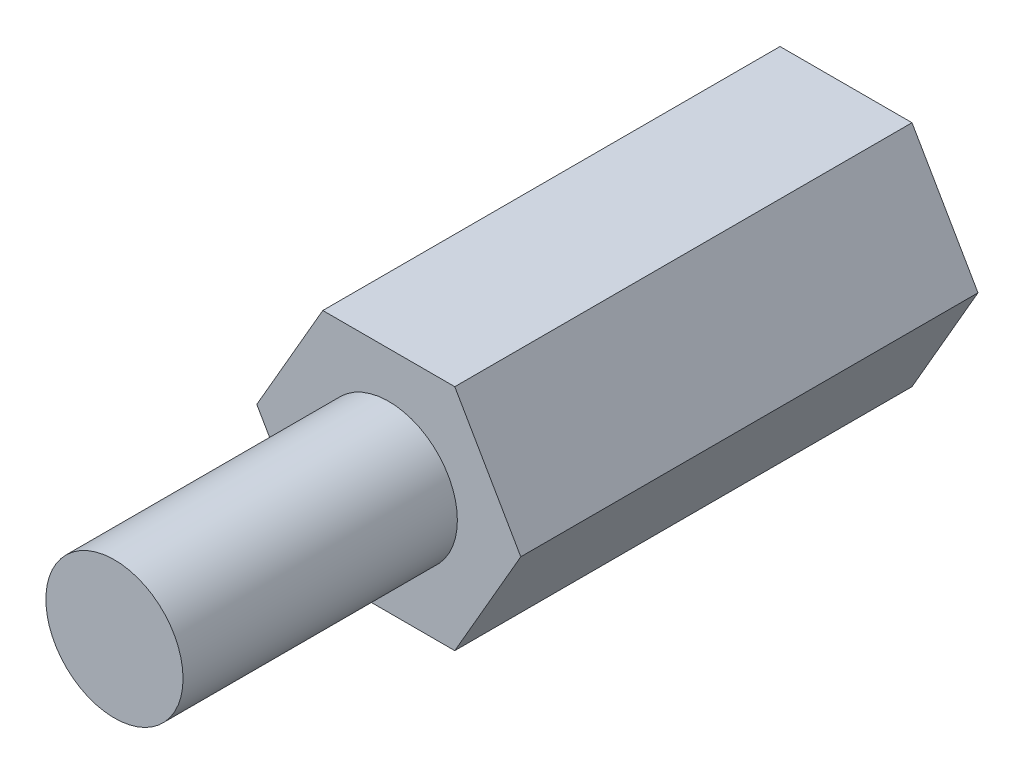
SolidWorks part; units mm, degrees
ref_plane "前视基准面" through (0, 0, 0) normal (0, 0, 1) x (1, 0, 0)
ref_plane "上视基准面" through (0, 0, 0) normal (0, 1, 0) x (1, 0, 0)
ref_plane "右视基准面" through (0, 0, 0) normal (1, 0, 0) x (0, 0, -1)
sketch "草图1" plane through (0, 0, 0) normal (0, 0, 1) x (1, 0, 0)
  line L0 (-28.6627, 0) -> (33.6774, 0) construction
  line L1 (1.4434, -2.5) -> (2.8868, 0)
  line L2 (2.8868, 0) -> (1.4434, 2.5)
  line L3 (1.4434, 2.5) -> (-1.4434, 2.5)
  line L4 (-1.4434, 2.5) -> (-2.8868, 0)
  line L5 (-2.8868, 0) -> (-1.4434, -2.5)
  line L6 (-1.4434, -2.5) -> (1.4434, -2.5)
  circle A0 centre (0, 0) radius 2.5 construction
  dimension "D1" = 5
extrude "拉伸1" add sketch "草图1" along normal blind 10
sketch "草图2" plane through (0, 0, 10) normal (0, 0, 1) x (1, 0, 0)
  circle A0 centre (0, 0) radius 1.5
  dimension "D1" = 3
extrude "拉伸2" add sketch "草图2" along normal blind 6
hole_wizard "M3x0.5 螺纹孔1" positions "3D草图2" profile "草图5" tap size "M3x0.5" standard "ISO"
sketch3d "3D草图2"
  point P0 (0, 0, 0)
  point P2 (0, 0, 0)
  point P3 (0, 0, 0)
  point P4 (0, 0, 0)
sketch "草图5" plane through (0, 0, 0) normal (1, 0, 0) x (0, 1, 0)
  line L0 (0, 0) -> (0, 11.7511)
  line L1 (0, 11.7511) -> (1.25, 11)
  line L2 (1.25, 11) -> (1.25, 0)
  line L5 (1.25, 0) -> (0, 0)
  line L10 (0, 11.7511) -> (-1.25, 11) construction
  line L11 (0, -6.35) -> (0, 107.95) construction
  dimension "蹟恇謂郰芛眻噤" = 2.5
  dimension "蹟恇謂郰芛旮僅" = 11
  dimension "絳芛褒僅" = 118
cosmetic thread "孔螺蚊线1" parameters "D1"=6, "D2"=3
cosmetic thread "孔螺蚊线2" parameters "D1"=6, "D2"=3
cosmetic thread "孔螺蚊线3" parameters "D1"=6, "D2"=3
cosmetic thread "孔螺蚊线4" parameters "D1"=6, "D2"=3
